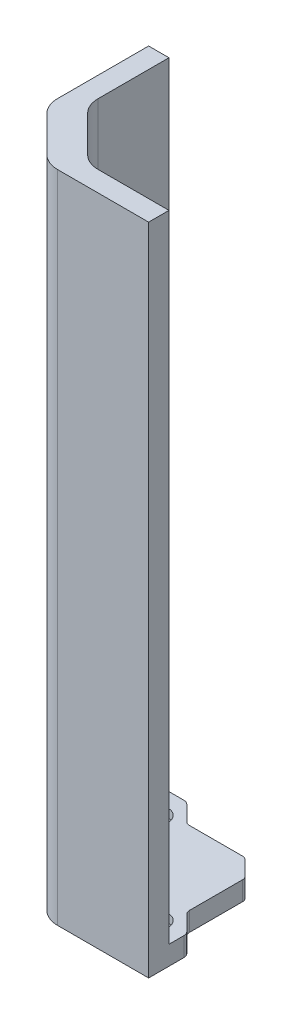
SolidWorks part; units mm, degrees
ref_plane "Alzado" through (0, 0, 0) normal (0, 0, 1) x (1, 0, 0)
ref_plane "Planta" through (0, 0, 0) normal (0, 1, 0) x (1, 0, 0)
ref_plane "Vista lateral" through (0, 0, 0) normal (1, 0, 0) x (0, 0, -1)
sketch "Sketch1" plane through (0, 0, 0) normal (0, 1, 0) x (1, 0, 0)
  line L0 (0, 0) -> (0, 60)
  line L1 (0, 60) -> (15, 60)
  line L2 (15, 60) -> (22.5, 52.5)
  line L3 (60, 15) -> (60, 0)
  line L4 (60, 0) -> (0, 0)
  line L5 (22.5, 52.5) -> (45.4289, 52.5)
  line L6 (52.5, 45.4289) -> (52.5, 22.5)
  line L7 (52.5, 52.5) -> (0, 0) construction
  line L8 (52.5, 22.5) -> (60, 15)
  line L9 (45.4289, 52.5) -> (52.5, 45.4289)
  dimension "D1" = 15
  dimension "D2" = 60
  dimension "D3" = 45
  dimension "D4" = 30
  dimension "D5" = 10
extrude "Boss-Extrude1" add sketch "Sketch1" along normal blind 7.5
fillet "Fillet1" radius 2.5 6 edges at (15, 3.75, -60) (60, 3.75, -15) (52.5, 3.75, -22.5) (22.5, 3.75, -52.5) (45.4289, 3.75, -52.5) (52.5, 3.75, -45.4289)
sketch "Sketch2" plane through (0, 7.5, 0) normal (0, 1, 0) x (1, 0, 0)
  line L0 (0, 60) -> (0, 0)
  line L1 (0, 0) -> (60, 0)
  line L2 (60, 0) -> (60, 8)
  line L3 (60, 0) -> (60, 13.9645) construction
  line L4 (60, 8) -> (8, 8)
  line L5 (8, 8) -> (8, 60)
  line L6 (13.9645, 60) -> (0, 60) construction
  line L7 (8, 60) -> (0, 60)
  line L8 (0, 25) -> (25, 25) construction
  line L9 (25, 25) -> (25, 0) construction
  dimension "D1" = 8
  dimension "D2" = 8
  dimension "D3" = 25
extrude "Boss-Extrude2" add sketch "Sketch2" along normal blind 250
chamfer "Chamfer1" distance 20 angle 45 2 edges at (0, 128.75, 0) (8, 132.5, -8)
fillet "Fillet2" radius 10 4 edges at (0, 128.75, -20) (20, 128.75, 0) (28, 132.5, -8) (8, 132.5, -28)
sketch "Sketch3" plane through (0, 7.5, 0) normal (0, 1, 0) x (1, 0, 0)
  line L0 (0, 25) -> (25, 25) construction
  line L1 (0, 60) -> (0, 24.1421) construction
  line L2 (25, 25) -> (25, 0) construction
  line L3 (24.1421, 0) -> (60, 0) construction
  line L4 (36.6, 13.4) -> (49.1879, 13.4) construction
  line L6 (36.6, 13.4) -> (25, 25) construction
  line L7 (25, 25) -> (0, 0) construction
  line L8 (60, 8) -> (32.1421, 8) construction
  circle A1 centre (36.6, 13.4) radius 2.7
  circle A2 centre (49.1879, 13.4) radius 2.7
  circle A3 centre (13.4, 49.1879) radius 2.7
  circle A4 centre (13.4, 36.6) radius 2.7
  point P12 (4.6585, 3.6844)
  point P14 (0, 0)
  dimension "D2" = 5.4
  dimension "D3" = 5.4
  dimension "D1" = 25
  dimension "D4" = 90
  dimension "D5" = 5.4
extrude "Cut-Extrude1" cut sketch "Sketch3" against normal through all
sketch "Sketch6" plane through (0, 7.5, 0) normal (0, 1, 0) x (1, 0, 0)
  point P0 (13.4, 49.1879)
  point P3 (13.4, 36.6)
  point P6 (36.6, 13.4)
  point P9 (49.1879, 13.4)
hole_wizard "Refrentado para tornillo con cabeza plana de M51" positions "Sketch6" profile "Sketch7" counterbore size "M5" standard "ISO" end condition through all
sketch "Sketch7" plane through (13.4, 7.5, -49.1879) normal (1, 0, 0) x (0, 0, 1)
  line L0 (0, 0) -> (0, 7.5)
  line L1 (0, 7.5) -> (2.65, 7.5)
  line L3 (2.65, 7.5) -> (2.65, 3.3)
  line L4 (2.65, 3.3) -> (5, 3.3)
  line L5 (5, 3.3) -> (5, 0)
  line L7 (5, 0) -> (0, 0)
  line L11 (0, -6.35) -> (0, 107.95) construction
  dimension "Diámetro de taladro hasta el siguiente" = 5.3
  dimension "Profundidad de taladro hasta el siguiente" = 7.5
  dimension "Diámetro de refrentado" = 10
  dimension "Profundidad de refrentado" = 3.3
